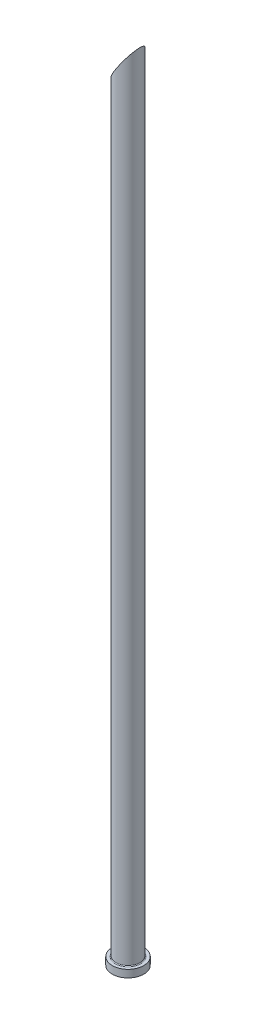
SolidWorks part; units mm, degrees
ref_plane "Front Plane" through (0, 0, 0) normal (0, 0, 1) x (1, 0, 0)
ref_plane "Top Plane" through (0, 0, 0) normal (0, 1, 0) x (1, 0, 0)
ref_plane "Right Plane" through (0, 0, 0) normal (1, 0, 0) x (0, 0, -1)
sketch "Sketch1" plane through (0, 0, 0) normal (0, 0, 1) x (1, 0, 0)
  line L0 (-0.4064, 28.4125) -> (-0.4064, 55.4879)
  line L1 (-0.4064, 33.7194) -> (-0.4064, 27.3694) construction
  line L2 (0, 30.8691) -> (0, 36.6705) construction
revolve "Revolve-Thin1" add sketch "Sketch1" angle 360 about L2
sketch "Sketch2" plane through (0, 0, 0) normal (0, 0, 1) x (1, 0, 0)
  line L0 (-2.9115, 50.1888) -> (1.641, 57.1764)
extrude "Cut-Extrude1" cut sketch "Sketch2" against normal through all and the other way through all
sketch "Sketch3" plane through (0, 28.4125, 0) normal (0, -1, 0) x (1, 0, 0)
  circle A2 centre (0, 0) radius 0.5334
  circle A3 centre (0, 0) radius 0.5334
  circle A4 centre (0, 0) radius 0.2794
  circle A5 centre (0, 0) radius 0.2794
  dimension "D1" = 0.127
  dimension "D2" = 0.127
extrude "Extrude1" add sketch "Sketch3" along normal blind 0.254
fillet "Fillet1" radius 0.0254 1 edges at (0, 28.4125, -0.4064)
